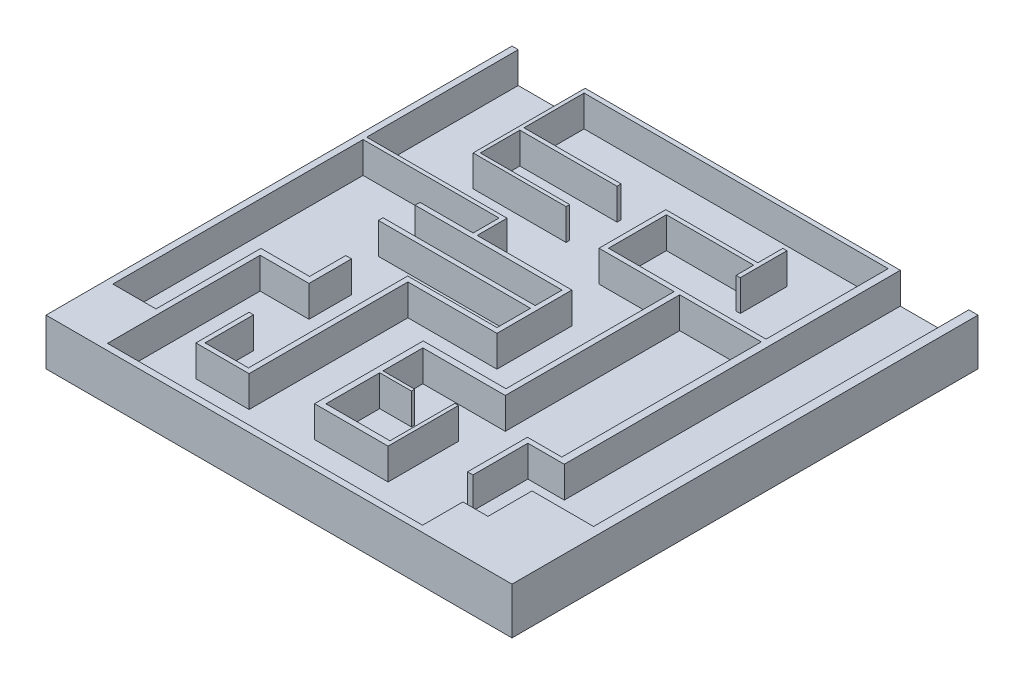
SolidWorks part; units mm, degrees
ref_plane "Front Plane" through (0, 0, 0) normal (0, 0, 1) x (1, 0, 0)
ref_plane "Top Plane" through (0, 0, 0) normal (0, 1, 0) x (1, 0, 0)
ref_plane "Right Plane" through (0, 0, 0) normal (1, 0, 0) x (0, 0, -1)
sketch "Sketch1" plane through (0, 0, 0) normal (0, 1, 0) x (1, 0, 0)
  line L1 (-150, -150) -> (150, -150)
  line L2 (-150, -150) -> (-150, 150)
  line L3 (-150, 150) -> (150, 150)
  line L4 (150, -150) -> (150, 150)
  line L5 (-150, -150) -> (150, 150) construction
  line L6 (-150, 150) -> (150, -150) construction
  point P0 (0, 0)
  dimension "D1" = 300
  dimension "D2" = 300
extrude "Boss-Extrude1" add sketch "Sketch1" along normal blind 10
sketch "Sketch2" plane through (0, 10, 0) normal (0, 1, 0) x (1, 0, 0)
  line L0 (-9.2738, 108.3067) -> (-9.2738, 65.3025)
  line L1 (-146.0019, 150) -> (-146.0019, 52.4313)
  line L4 (150, -150) -> (150, 150)
  line L5 (150, 150) -> (-150, 150)
  line L6 (-150, 150) -> (-150, -150)
  line L7 (-150, -150) -> (150, -150)
  line L8 (150, -150) -> (150, 150)
  line L9 (150, 150) -> (144.1013, 150)
  line L10 (-150, 150) -> (-150, -150)
  line L11 (-150, -150) -> (150, -150)
  line L14 (104.4787, -91.5844) -> (104.4787, -119.9656)
  line L15 (-14.17, -112.9522) -> (-14.17, -42.9788)
  line L16 (42.6503, 65.3025) -> (95.1849, 65.3025)
  line L19 (-51.9911, -117.2698) -> (-86.2462, -117.2698)
  line L25 (-146.0019, 52.4313) -> (-55.6518, 52.4313)
  line L26 (99.9828, -66.3209) -> (99.9828, 150)
  line L27 (-92.4599, 33.2507) -> (-58.2852, 33.2507) construction
  line L29 (88.3456, -119.9656) -> (104.4787, -119.9656)
  line L30 (-55.6518, 33.2507) -> (5.3133, 33.2507)
  line L33 (-118.0215, -43.6145) -> (-118.0215, -111.1747)
  line L46 (144.1013, 150) -> (144.1013, -91.5844)
  line L52 (-100.595, 147.0032) -> (-100.595, 108.3067)
  line L53 (-43.0921, 80.2078) -> (-100.595, 80.2078)
  line L54 (-43.0921, 80.2078) -> (-43.0921, 77.9013)
  line L55 (-43.0921, 77.9013) -> (-102.9351, 77.9013)
  line L57 (-37.9897, 108.3067) -> (-100.595, 108.3067)
  line L58 (-37.9897, 108.3067) -> (-37.9897, 105.6508)
  line L59 (-37.9897, 105.6508) -> (-100.595, 105.6508)
  line L64 (-6.2323, 105.6508) -> (-6.2323, 68.3753)
  line L65 (49.9714, 108.3067) -> (-9.2738, 108.3067)
  line L67 (49.9714, 105.6508) -> (-6.2323, 105.6508)
  line L69 (-6.2323, 68.3753) -> (95.1849, 68.3753)
  line L71 (-9.2738, 65.3025) -> (39.1097, 65.3025)
  line L74 (39.1097, 65.3025) -> (39.1097, -42.9788)
  line L76 (42.6503, 65.3025) -> (42.6503, -46.9783)
  line L77 (39.1097, -42.9788) -> (-14.17, -42.9788)
  line L79 (42.6503, -46.9783) -> (-10.4234, -46.9783)
  line L82 (-10.4234, -46.9783) -> (-10.4234, -72.6137)
  line L86 (2.1632, 30.0934) -> (2.1632, 12.7824)
  line L87 (-51.9911, -15.0097) -> (5.3133, -15.0097)
  line L88 (5.3133, 33.2507) -> (5.3133, -15.0097)
  line L89 (-92.4599, 33.2507) -> (-58.2852, 33.2507)
  line L90 (-92.4599, 33.2507) -> (-92.4599, 30.0934)
  line L91 (-92.4599, 30.0934) -> (2.1632, 30.0934)
  line L93 (-95.832, 12.7824) -> (2.1632, 12.7824)
  line L94 (-95.832, 12.7824) -> (-95.832, 9.7647)
  line L95 (-95.832, 9.7647) -> (2.1632, 9.7647)
  line L97 (-55.3775, -11.7799) -> (2.1632, -11.7799)
  line L102 (-51.9911, -15.0097) -> (-51.9911, -117.2698)
  line L104 (-55.3775, -11.7799) -> (-55.3775, -114.2772)
  line L106 (-55.6518, 33.2507) -> (-55.6518, 52.4313)
  line L108 (-58.2852, 33.2507) -> (-58.2852, 49.9405)
  line L111 (-145.8023, 49.9405) -> (-58.2852, 49.9405)
  line L113 (-86.7104, -20.291) -> (-83.0084, -20.291)
  line L114 (-86.7104, -20.291) -> (-86.7104, -43.6145)
  line L116 (-83.0084, -20.291) -> (-83.0084, -47.6975)
  line L117 (-86.7104, -43.6145) -> (-118.0215, -43.6145)
  line L119 (-83.0084, -47.6975) -> (-114.4526, -47.6975)
  line L122 (-114.4526, -47.6975) -> (-114.4526, -145.9453)
  line L125 (-145.8023, -111.1747) -> (-118.0215, -111.1747)
  line L133 (-86.2462, -83.0465) -> (-83.3358, -83.0465)
  line L136 (-83.3358, -83.0465) -> (-83.3358, -114.2772)
  line L137 (30.8021, -109.3467) -> (-10.4234, -109.3467)
  line L139 (33.1516, -112.9522) -> (-14.17, -112.9522)
  line L140 (-86.2462, -83.0465) -> (-86.2462, -117.2698)
  line L141 (-10.4234, -72.6137) -> (9.9573, -72.6137)
  line L143 (-10.4234, -74.7305) -> (9.9573, -74.7305)
  line L144 (9.9573, -72.6137) -> (9.9573, -74.7305)
  line L145 (30.8021, -67.5668) -> (33.1516, -67.5668)
  line L146 (30.8021, -67.5668) -> (30.8021, -109.3467)
  line L148 (33.1516, -67.5668) -> (33.1516, -112.9522)
  line L149 (73.0707, -101.6681) -> (76.5345, -101.6681)
  line L150 (73.0707, -101.6681) -> (73.0707, -63.1235)
  line L152 (76.5345, -101.6681) -> (76.5345, -66.3209)
  line L153 (73.0707, -63.1235) -> (95.1849, -63.1235)
  line L155 (76.5345, -66.3209) -> (99.9828, -66.3209)
  line L160 (95.1849, -63.1235) -> (95.1849, 65.3025)
  line L161 (49.9714, 124.3627) -> (52.6009, 124.3627)
  line L162 (49.9714, 124.3627) -> (49.9714, 108.3067)
  line L163 (49.9714, 94.3425) -> (52.6009, 94.3425)
  line L164 (52.6009, 124.3627) -> (52.6009, 94.3425)
  line L165 (144.1013, -91.5844) -> (104.4787, -91.5844)
  line L178 (88.3456, -119.9656) -> (88.3456, -145.9453)
  line L182 (95.1849, 68.3753) -> (95.1849, 147.0032)
  line L185 (49.9714, 105.6508) -> (49.9714, 94.3425)
  line L186 (-10.4234, -74.7305) -> (-10.4234, -109.3467)
  line L190 (-55.3775, -114.2772) -> (-83.3358, -114.2772)
  line L193 (2.1632, 9.7647) -> (2.1632, -11.7799)
  line L196 (-100.595, 105.6508) -> (-100.595, 80.2078)
  line L198 (-102.9351, 77.9013) -> (-102.9351, 150)
  line L200 (-146.0019, 150) -> (-150, 150)
  line L201 (99.9828, 150) -> (-102.9351, 150)
  line L204 (-114.4526, -145.9453) -> (88.3456, -145.9453)
  line L205 (-145.8023, 49.9405) -> (-145.8023, -111.1747)
  line L206 (-100.595, 147.0032) -> (95.1849, 147.0032)
  dimension "D1" = 0
extrude "Boss-Extrude4" add sketch "Sketch2" along normal blind 20
